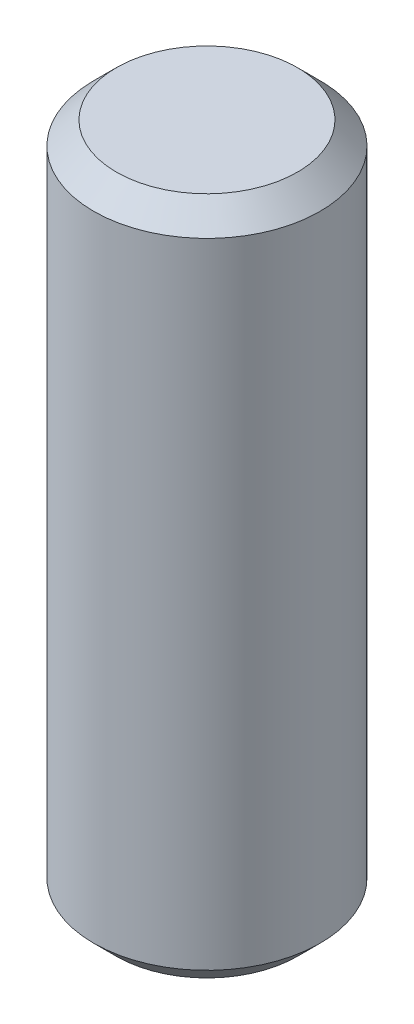
SolidWorks part; units mm, degrees
material "Commercially Pure titanium (Ti-55)  UNS R50550*"
ref_plane "Front Plane" through (0, 0, 0) normal (0, 0, 1) x (1, 0, 0)
ref_plane "Top Plane" through (0, 0, 0) normal (0, 1, 0) x (1, 0, 0)
ref_plane "Right Plane" through (0, 0, 0) normal (1, 0, 0) x (0, 0, -1)
sketch "Sketch2" plane through (0, 0, 0) normal (0, 1, 0) x (1, 0, 0)
  circle A0 centre (0, 0) radius 0.5
  dimension "D1" = 1
extrude "Boss-Extrude1" add sketch "Sketch2" along normal blind 3
chamfer "Chamfer1" distance 0.1 angle 45 2 edges at (0, 0, 0.5) (0, 3, 0.5)
